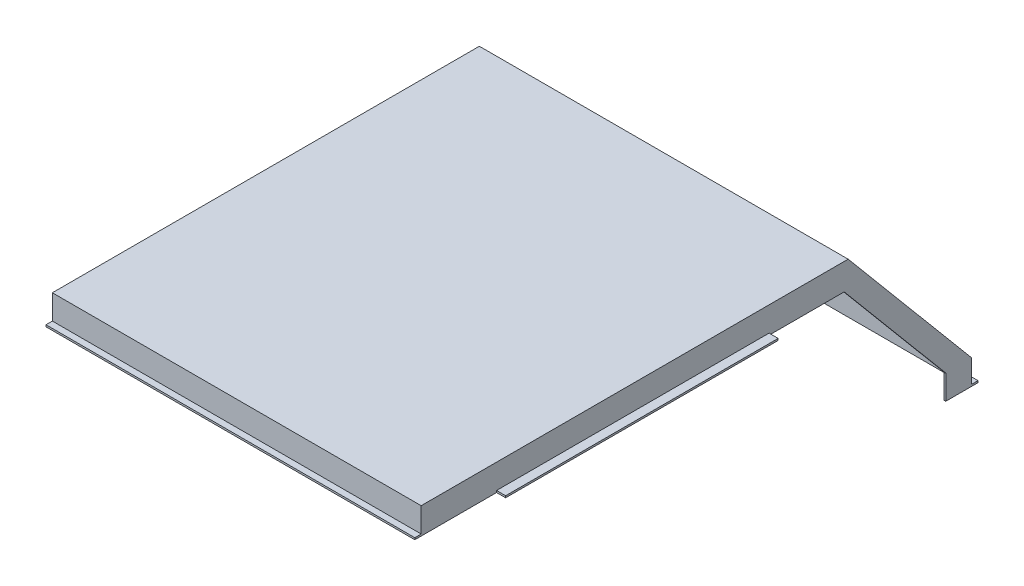
SolidWorks part; units mm, degrees
ref_plane "Front Plane" through (0, 0, 0) normal (0, 0, 1) x (1, 0, 0)
ref_plane "Top Plane" through (0, 0, 0) normal (0, 1, 0) x (1, 0, 0)
ref_plane "Right Plane" through (0, 0, 0) normal (1, 0, 0) x (0, 0, -1)
sketch "Sketch2" plane through (0, 0, 0) normal (1, 0, 0) x (0, 0, -1)
  line L15 (-48.0387, 0) -> (416.8844, 0) construction
  line L22 (-49.5387, 1.5) -> (-49.5387, -25.5)
  line L24 (-49.5387, 1.5) -> (417.5839, 1.5)
  line L25 (-48.0387, 0) -> (-48.0387, -25.5) construction
  line L30 (416.8844, 0) -> (550.9613, -159.7866) construction
  line L36 (417.5839, 1.5) -> (552.4613, -159.2406)
  line L37 (552.4613, -159.2406) -> (552.4613, -185.7406)
  line L38 (552.4613, -185.7406) -> (561.4613, -185.7406)
  line L40 (-49.5387, -25.5) -> (-58.5387, -25.5)
  line L42 (554.4613, -183.7406) -> (561.4613, -183.7406)
  line L43 (554.4613, -158.5127) -> (554.4613, -183.7406)
  line L44 (418.5165, 3.5) -> (554.4613, -158.5127)
  line L45 (-51.5387, 3.5) -> (418.5165, 3.5)
  line L46 (-51.5387, 3.5) -> (-51.5387, -23.5)
  line L47 (-51.5387, -23.5) -> (-58.5387, -23.5)
  line L48 (561.4613, -183.7406) -> (561.4613, -185.7406)
  line L49 (-58.5387, -23.5) -> (-58.5387, -25.5)
  line L53 (550.9613, -159.7866) -> (550.9613, -185.7406) construction
  line L54 (416.8844, 0) -> (550.9613, -159.7866) construction
  line L55 (550.9613, -159.7866) -> (550.9613, -186.5185) construction
  dimension "D1" = 1.5
  dimension "D2" = 2
  dimension "D3" = 1.5
extrude "Boss-Extrude1" add sketch "Sketch2" along normal blind 203
sketch "Sketch4" plane through (0, 1.5, 0) normal (0, -1, 0) x (-1, 0, 0)
  line L0 (-203, 417.5839) -> (0, 417.5839) construction
  line L1 (-203, -49.5387) -> (-201, -49.5387)
  line L2 (-203, -49.5387) -> (-203, 417.5839)
  line L3 (-203, 417.5839) -> (-201, 417.5839)
  line L4 (-201, -49.5387) -> (-201, 417.5839)
extrude "Boss-Extrude4" add sketch "Sketch4" along direction (0, -1, 0) on the side of the normal blind 27
sketch "Sketch5" plane through (0, 206.2397, -245.7869) normal (0, -0.6428, 0.766) x (1, 0, 0)
  line L0 (201, -267.2687) -> (0, -267.2687) construction
  line L1 (203, -477.1006) -> (201, -477.1006)
  line L2 (203, -477.1006) -> (203, -267.2687)
  line L3 (203, -267.2687) -> (201, -267.2687)
  line L4 (201, -477.1006) -> (201, -267.2687)
extrude "Boss-Extrude5" add sketch "Sketch5" along normal blind 20
sketch "Sketch6" plane through (0, 0, -552.4613) normal (0, 0, 1) x (1, 0, 0)
  line L0 (201, -159.2406) -> (0, -159.2406) construction
  line L1 (203, -185.7406) -> (201, -185.7406)
  line L2 (203, -185.7406) -> (203, -159.2406)
  line L3 (203, -159.2406) -> (201, -159.2406)
  line L4 (201, -185.7406) -> (201, -159.2406)
extrude "Boss-Extrude6" add sketch "Sketch6" along normal blind 26.5
sketch "Sketch14" plane through (203, 0, 0) normal (1, 0, 0) x (0, 0, -1)
  line L0 (414.1314, -25.5) -> (-58.5387, -25.5) construction
  line L1 (31.4613, -25.5) -> (331.4613, -25.5)
  line L2 (31.4613, -25.5) -> (31.4613, -23.5)
  line L3 (31.4613, -23.5) -> (331.4613, -23.5)
  line L4 (331.4613, -25.5) -> (331.4613, -23.5)
  line L5 (-51.5387, 3.5) -> (-51.5387, -23.5) construction
  dimension "D1" = 83
extrude "Boss-Extrude10" add sketch "Sketch14" along normal blind 10
mirror "Mirror3" about plane through (0, 0, 0) normal (1, 0, 0) of "Boss-Extrude10", "Boss-Extrude1", "Boss-Extrude4", "Boss-Extrude5", "Boss-Extrude6"
sketch "Sketch8" plane through (0, 3.5, 0) normal (0, 1, 0) x (1, 0, 0)
  line L9 (-203, 561.4613) -> (-153, 561.4613)
  line L10 (-203, 561.4613) -> (-203, 484.4613)
  line L11 (-203, 484.4613) -> (-153, 484.4613)
  line L12 (-153, 561.4613) -> (-153, 484.4613)
extrude "Cut-Extrude1" cut sketch "Sketch8" along direction (0, 1, 0) on the side against the normal up to next (189.2406 mm away)
sketch "Sketch10" plane through (-201, 0, 0) normal (1, 0, 0) x (0, 0, -1)
  line L0 (484.4613, -109.3158) -> (484.4613, -78.2014)
  line L1 (484.4613, -109.3158) -> (483.1757, -107.7838)
  line L2 (484.4613, -78.2014) -> (483.1757, -76.6693)
  line L3 (483.1757, -107.7838) -> (483.1757, -76.6693)
  line L4 (417.5839, 1.5) -> (484.4613, -78.2014) construction
extrude "Boss-Extrude7" add sketch "Sketch10" along direction (1, 0, 0) on the side of the normal blind 48
sketch "Sketch11" plane through (0, 206.2397, -245.7869) normal (0, -0.6428, 0.766) x (1, 0, 0)
  line L0 (201, -477.1006) -> (-153, -477.1006) construction
  line L1 (-151, -477.1006) -> (-153, -477.1006)
  line L2 (-151, -477.1006) -> (-151, -369.3114)
  line L3 (-151, -369.3114) -> (-153, -369.3114)
  line L4 (-153, -477.1006) -> (-153, -369.3114)
extrude "Boss-Extrude8" add sketch "Sketch11" along normal blind 20
sketch "Sketch12" plane through (-153, 0, 0) normal (-1, 0, 0) x (0, 0, 1)
  line L0 (-483.1757, -76.6693) -> (-483.1757, -107.7838)
  line L1 (-483.1757, -107.7838) -> (-467.8548, -89.525)
  line L2 (-467.8548, -89.525) -> (-483.1757, -76.6693)
extrude "Cut-Extrude2" cut sketch "Sketch12" along direction (-1, 0, 0) on the side against the normal up to next (2 mm away)
sketch "Sketch13" plane through (0, 0, -552.4613) normal (0, 0, 1) x (1, 0, 0)
  line L0 (201, -159.2406) -> (-151, -159.2406) construction
  line L1 (-153, -185.7406) -> (-151, -185.7406)
  line L2 (-153, -185.7406) -> (-153, -159.2406)
  line L3 (-153, -159.2406) -> (-151, -159.2406)
  line L4 (-151, -185.7406) -> (-151, -159.2406)
extrude "Boss-Extrude9" add sketch "Sketch13" along normal up to vertex (15.3209 mm away)
